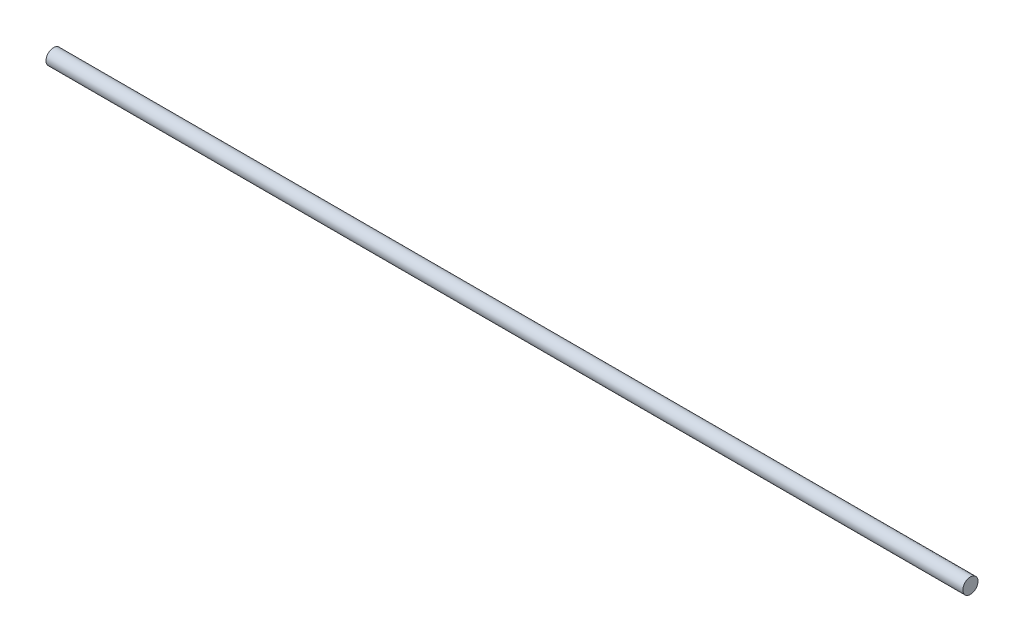
SolidWorks part; units mm, degrees
ref_plane "Alzado" through (0, 0, 0) normal (0, 0, 1) x (1, 0, 0)
ref_plane "Planta" through (0, 0, 0) normal (0, 1, 0) x (1, 0, 0)
ref_plane "Vista lateral" through (0, 0, 0) normal (1, 0, 0) x (0, 0, -1)
sketch "Croquis1" plane through (0, 0, 0) normal (1, 0, 0) x (0, 0, -1)
  circle A0 centre (0, 0) radius 4
extrude "Saliente-Extruir1" add sketch "Croquis1" along normal mid plane 482.37
